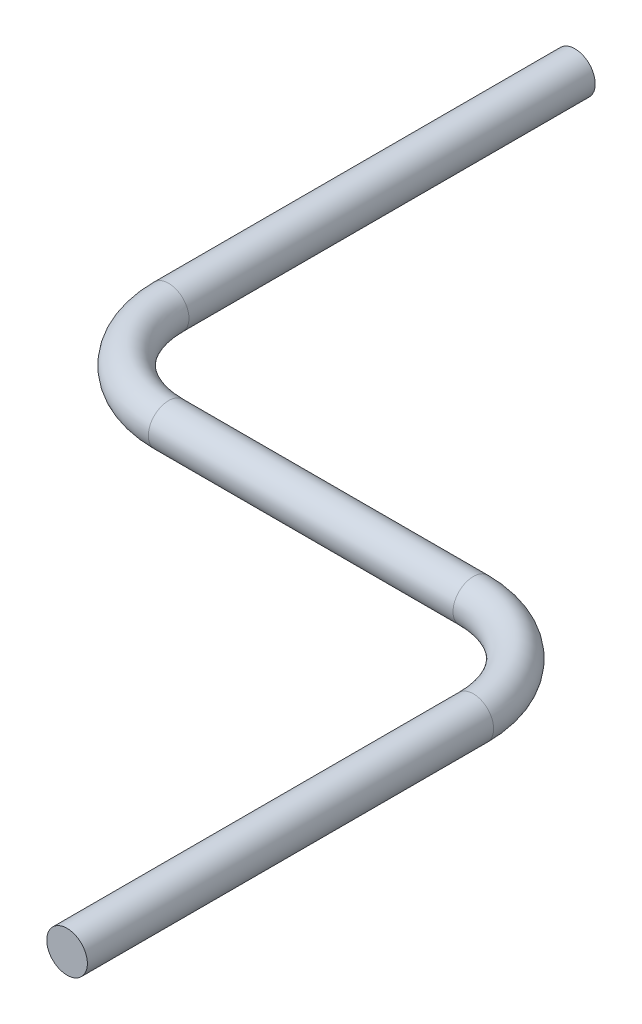
SolidWorks part; units mm, degrees
ref_plane "正面" through (0, 0, 0) normal (0, 0, 1) x (1, 0, 0)
ref_plane "平面" through (0, 0, 0) normal (0, 1, 0) x (1, 0, 0)
ref_plane "右側面" through (0, 0, 0) normal (1, 0, 0) x (0, 0, -1)
sketch "ｽｹｯﾁ1" plane through (0, 0, 0) normal (0, 0, 1) x (1, 0, 0)
  circle A0 centre (0, 0) radius 2
  dimension "D1" = 4
sketch "ｽｹｯﾁ2" plane through (0, 0, 0) normal (0, 1, 0) x (1, 0, 0)
  line L0 (0, 0) -> (0, -40)
  line L1 (10, -50) -> (40, -50)
  line L2 (50, -60) -> (50, -100)
  line L3 (-2, 0) -> (2, 0) construction
  line L4 (-2, 0) -> (2, 0)
  arc A0 (0, -40) -> (10, -50) centre (10, -40) ccw
  arc A1 (40, -50) -> (50, -60) centre (40, -60) cw
  dimension "D1" = 10
  dimension "D2" = 10
  dimension "D3" = 50
  dimension "D4" = 40
  dimension "D5" = 40
sweep "ｽｲｰﾌﾟ1" add profiles "ｽｹｯﾁ1" path "ｽｹｯﾁ2"
